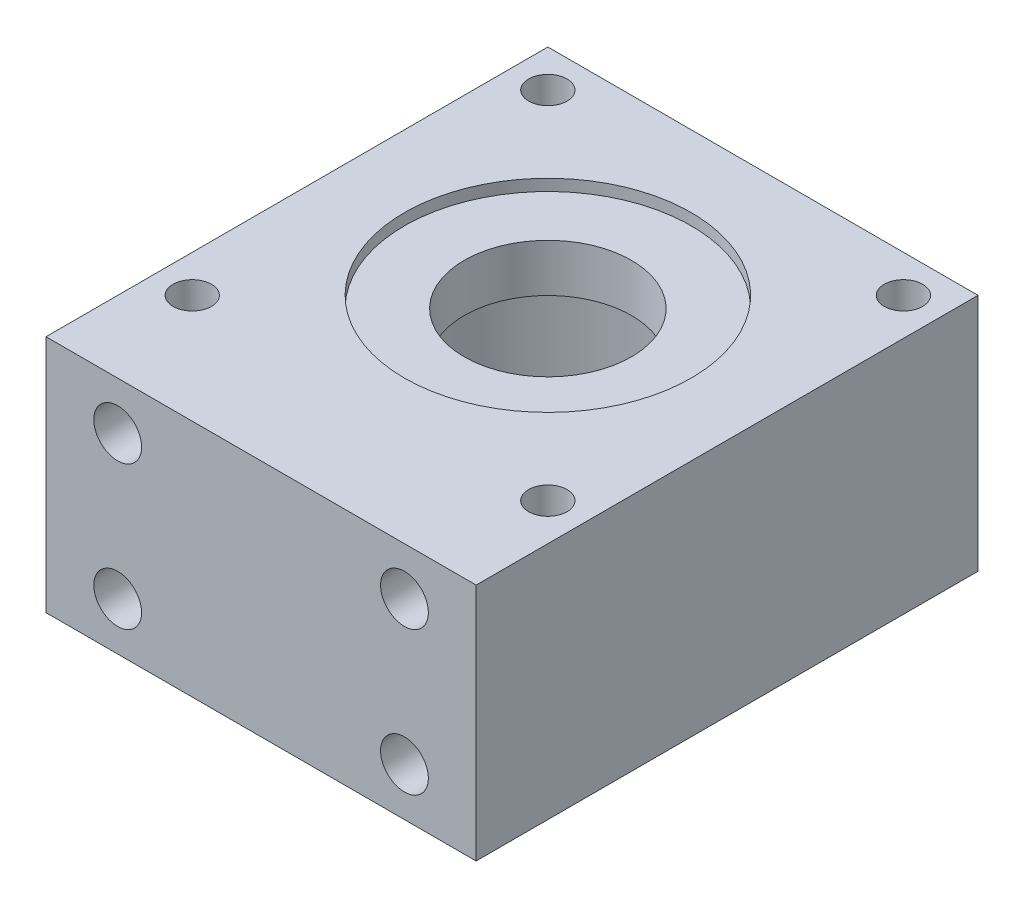
SolidWorks part; units mm, degrees
material "6061 Alloy"
ref_plane "Front" through (0, 0, 0) normal (0, 0, 1) x (1, 0, 0)
ref_plane "Top" through (0, 0, 0) normal (0, 1, 0) x (1, 0, 0)
ref_plane "Right" through (0, 0, 0) normal (1, 0, 0) x (0, 0, -1)
sketch "Sketch1" plane through (0, 0, 0) normal (0, 1, 0) x (1, 0, 0)
  line L0 (28.575, 28.575) -> (-28.575, 28.575)
  line L1 (-28.575, 28.575) -> (28.575, 28.575) construction
  line L2 (-28.575, 28.575) -> (-28.575, -28.575)
  line L3 (-28.575, -28.575) -> (28.575, -28.575) construction
  line L4 (28.575, 28.575) -> (28.575, -28.575)
  line L5 (-28.575, 28.575) -> (28.575, -28.575) construction
  line L6 (-28.575, -28.575) -> (28.575, 28.575) construction
  line L7 (-23.622, 23.622) -> (23.622, 23.622) construction
  line L8 (-23.622, 23.622) -> (-23.622, -23.622) construction
  line L9 (-23.622, -23.622) -> (23.622, -23.622) construction
  line L10 (23.622, 23.622) -> (23.622, -23.622) construction
  line L11 (-23.622, 23.622) -> (23.622, -23.622) construction
  line L12 (-23.622, -23.622) -> (23.622, 23.622) construction
  line L15 (-28.575, -28.575) -> (-28.575, -38.1)
  line L16 (-28.575, -38.1) -> (28.575, -38.1)
  line L17 (28.575, -38.1) -> (28.575, -28.575)
  circle A0 centre (23.622, -23.622) radius 2.5527
  circle A1 centre (23.622, 23.622) radius 2.5527
  circle A2 centre (-23.622, 23.622) radius 2.5527
  circle A3 centre (-23.622, -23.622) radius 2.5527
  point P0 (0, 0)
  point P6 (0, 0)
  dimension "D3" = 5.1054
  dimension "D1" = 57.15
  dimension "D2" = 47.244
  dimension "D4" = 9.525
extrude "Boss-Extrude1" add sketch "Sketch1" along normal blind 31.75
sketch "Sketch2" plane through (0, 31.75, 0) normal (0, 1, 0) x (1, 0, 0)
  circle A0 centre (0, 0) radius 19.05
  dimension "D1" = 38.1
extrude "Cut-Extrude1" cut sketch "Sketch2" against normal blind 1.524
sketch "Sketch3" plane through (0, 30.226, 0) normal (0, 1, 0) x (1, 0, 0)
  circle A0 centre (0, 0) radius 11.1125
  dimension "D1" = 22.225
extrude "Cut-Extrude2" cut sketch "Sketch3" against normal through all
sketch "Sketch4" plane through (0, 0, 0) normal (0, -1, 0) x (1, 0, 0)
  line L0 (0, 0) -> (0, 28.575) construction
  line L2 (0, 0) -> (13.0457, 20.2994) construction
  line L5 (-28.575, 28.575) -> (28.575, 28.575) construction
  circle A0 centre (0, 0) radius 21.844 construction
  circle A1 centre (0, 0) radius 24.13 construction
  arc A2 (0, 20.955) -> (2.8224, 22.6758) centre (0, 24.13) ccw
  arc A3 (11.3291, 17.6285) -> (9.8851, 20.602) centre (13.0457, 20.2994) cw
  arc A4 (2.8224, 22.6758) -> (9.8851, 20.602) centre (6.1542, 20.9592) cw
  arc A5 (11.3291, 17.6285) -> (14.6338, 17.5502) centre (13.0457, 20.2994) ccw
  arc A6 (14.6338, 17.5502) -> (19.4542, 11.9872) centre (16.5086, 14.3048) cw
  arc A7 (19.0613, 8.705) -> (19.4542, 11.9872) centre (21.9494, 10.024) cw
  arc A8 (19.0613, 8.705) -> (21.7991, 6.8525) centre (21.9494, 10.024) ccw
  arc A9 (21.7991, 6.8525) -> (22.8467, -0.4334) centre (21.6217, 3.1087) cw
  arc A10 (20.7417, -2.9822) -> (22.8467, -0.4334) centre (23.8844, -3.4341) cw
  arc A11 (20.7417, -2.9822) -> (22.0433, -6.0208) centre (23.8844, -3.4341) ccw
  arc A12 (22.0433, -6.0208) -> (18.9855, -12.7165) centre (19.87, -9.0743) cw
  arc A13 (15.8367, -13.7226) -> (18.9855, -12.7165) centre (18.2362, -15.8018) cw
  arc A14 (15.8367, -13.7226) -> (15.289, -16.9825) centre (18.2362, -15.8018) ccw
  arc A15 (15.289, -16.9825) -> (9.0966, -20.9621) centre (11.8098, -18.3763) cw
  arc A16 (5.9037, -20.1062) -> (9.0966, -20.9621) centre (6.7982, -23.1526) cw
  arc A17 (5.9037, -20.1062) -> (3.6804, -22.5524) centre (6.7982, -23.1526) ccw
  arc A18 (3.6804, -22.5524) -> (-3.6804, -22.5524) centre (0, -21.844) cw
  arc A19 (-5.9037, -20.1062) -> (-3.6804, -22.5524) centre (-6.7982, -23.1526) cw
  arc A20 (-5.9037, -20.1062) -> (-9.0966, -20.9621) centre (-6.7982, -23.1526) ccw
  arc A21 (-9.0966, -20.9621) -> (-15.289, -16.9825) centre (-11.8098, -18.3763) cw
  arc A22 (-15.8367, -13.7226) -> (-15.289, -16.9825) centre (-18.2362, -15.8018) cw
  arc A23 (-15.8367, -13.7226) -> (-18.9855, -12.7165) centre (-18.2362, -15.8018) ccw
  arc A24 (-18.9855, -12.7165) -> (-22.0433, -6.0208) centre (-19.87, -9.0743) cw
  arc A25 (-20.7417, -2.9822) -> (-22.0433, -6.0208) centre (-23.8844, -3.4341) cw
  arc A26 (-20.7417, -2.9822) -> (-22.8467, -0.4334) centre (-23.8844, -3.4341) ccw
  arc A27 (-22.8467, -0.4334) -> (-21.7991, 6.8525) centre (-21.6217, 3.1087) cw
  arc A28 (-19.0613, 8.705) -> (-21.7991, 6.8525) centre (-21.9494, 10.024) cw
  arc A29 (-19.0613, 8.705) -> (-19.4542, 11.9872) centre (-21.9494, 10.024) ccw
  arc A30 (-19.4542, 11.9872) -> (-14.6338, 17.5502) centre (-16.5086, 14.3048) cw
  arc A31 (-11.3291, 17.6285) -> (-14.6338, 17.5502) centre (-13.0457, 20.2994) cw
  arc A32 (-11.3291, 17.6285) -> (-9.8851, 20.602) centre (-13.0457, 20.2994) ccw
  arc A33 (-9.8851, 20.602) -> (-2.8224, 22.6758) centre (-6.1542, 20.9592) cw
  arc A34 (0, 20.955) -> (-2.8224, 22.6758) centre (0, 24.13) cw
  point P14 (0, 28.575)
  point P87 (0, 0)
  dimension "D1" = 48.26
  dimension "D2" = 43.688
  dimension "D4" = 3.175
  dimension "D5" = 3.175
  dimension "D3" = 32.727
  dimension "D6" = 11
extrude "Cut-Extrude3" cut sketch "Sketch4" against normal blind 23.876
sketch "Sketch5" plane through (0, 0, 0) normal (0, -1, 0) x (1, 0, 0)
  circle A0 centre (0, 0) radius 26.1937
  dimension "D1" = 52.3875
extrude "Cut-Extrude4" cut sketch "Sketch5" against normal blind 17.526
sketch "Sketch7" plane through (0, 0, 0) normal (0, -1, 0) x (1, 0, 0)
  line L0 (-28.575, -28.575) -> (28.575, -28.575) construction
  line L4 (-28.575, -28.575) -> (-28.575, 38.1) construction
  line L5 (-23.8125, 26.9875) -> (23.8125, 26.9875)
  line L6 (-26.9875, 23.8125) -> (-26.9875, -23.8125)
  line L7 (-23.8125, -26.9875) -> (23.8125, -26.9875)
  line L8 (26.9875, 23.8125) -> (26.9875, -23.8125)
  line L9 (-26.9875, 26.9875) -> (26.9875, -26.9875) construction
  line L10 (-26.9875, -26.9875) -> (26.9875, 26.9875) construction
  arc A0 (-26.9875, -23.8125) -> (-23.8125, -26.9875) centre (-23.8125, -23.8125) ccw
  arc A2 (23.8125, -26.9875) -> (26.9875, -23.8125) centre (23.8125, -23.8125) ccw
  arc A3 (23.8125, 26.9875) -> (26.9875, 23.8125) centre (23.8125, 23.8125) cw
  arc A4 (-23.8125, 26.9875) -> (-26.9875, 23.8125) centre (-23.8125, 23.8125) ccw
  point P0 (0, 0)
  dimension "D1" = 1.5875
  dimension "D3" = 3.175
  dimension "D2" = 1.5875
extrude "Cut-Extrude5" cut sketch "Sketch7" against normal blind 3.175
ref_plane "Plane1" through (0, 0, 28.575) normal (0, 0, 1) x (1, 0, 0)
sketch "Sketch10" plane through (0, 0, 38.1) normal (0, 0, 1) x (1, 0, 0)
  line L0 (28.575, 31.75) -> (28.575, 0) construction
  line L1 (19.05, 25.4) -> (-19.05, 25.4)
  line L2 (19.05, 25.4) -> (19.05, 6.35)
  line L3 (19.05, 6.35) -> (-19.05, 6.35)
  line L4 (-19.05, 25.4) -> (-19.05, 6.35)
  line L5 (19.05, 25.4) -> (-19.05, 6.35) construction
  line L6 (19.05, 6.35) -> (-19.05, 25.4) construction
  line L7 (-28.575, 0) -> (28.575, 0) construction
  point P0 (0, 15.875)
  point P7 (28.575, 15.875)
  point P10 (0, 0)
  dimension "D1" = 38.1
  dimension "D2" = 19.05
hole_wizard "1/4-20 Tapped Hole1" positions "Sketch12" profile "Sketch11" tap size "1/4-20" standard "ANSI Inch"
sketch "Sketch12" plane through (0, 0, 38.1) normal (0, 0, 1) x (1, 0, 0)
  point P0 (-19.05, 25.4)
  point P3 (19.05, 25.4)
  point P6 (19.05, 6.35)
  point P9 (-19.05, 6.35)
sketch "Sketch11" plane through (-19.05, 25.4, 38.1) normal (1, 0, 0) x (0, -1, 0)
  line L0 (0, 0) -> (0, 11.1858)
  line L1 (0, 11.1858) -> (2.5527, 9.652)
  line L2 (2.5527, 9.652) -> (2.5527, 9.525)
  line L3 (2.5527, 9.525) -> (3.175, 9.525)
  line L4 (3.175, 9.525) -> (3.175, 0)
  line L5 (3.175, 0) -> (0, 0)
  line L10 (0, 11.1858) -> (-2.5527, 9.652) construction
  line L11 (0, -6.35) -> (0, 107.95) construction
  dimension "Tap Drill Dia." = 5.1054
  dimension "Tap Drill Depth" = 9.652
  dimension "Thread Major Dia." = 6.35
  dimension "Thread Depth" = 9.525
  dimension "Drill Angle" = 118
